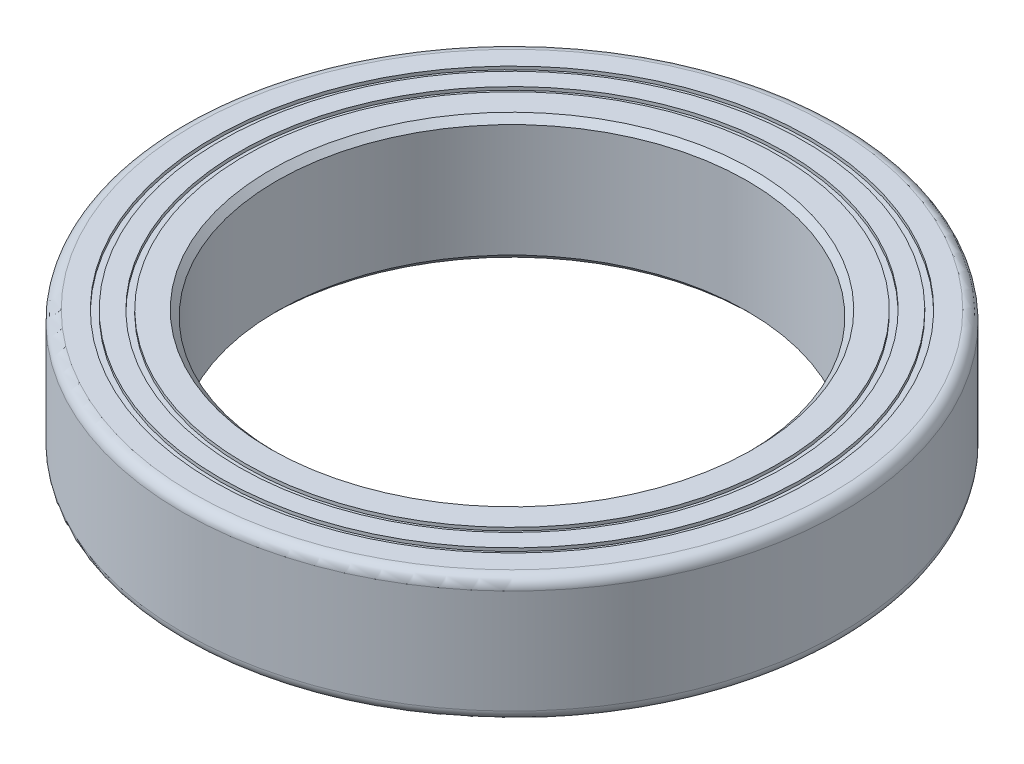
SolidWorks part; units mm, degrees
ref_plane "Front Plane" through (0, 0, 0) normal (0, 0, 1) x (1, 0, 0)
ref_plane "Top Plane" through (0, 0, 0) normal (0, 1, 0) x (1, 0, 0)
ref_plane "Right Plane" through (0, 0, 0) normal (1, 0, 0) x (0, 0, -1)
sketch "Sketch1" plane through (0, 0, 0) normal (0, 0, 1) x (1, 0, 0)
  line L0 (0, 0) -> (7.5, 0) construction
  line L1 (10.5, 0) -> (10.5, 4)
  line L3 (0, 2) -> (0, 0) construction
  line L4 (7.5, 0) -> (7.5, 4)
  line L5 (7.5, 0) -> (8.5, 0)
  line L6 (8.5, 0) -> (8.5, 0.1)
  line L7 (8.5, 0.1) -> (8.7, 0.1)
  line L8 (8.7, 0.1) -> (8.7, 0)
  line L9 (8.7, 0) -> (9.3, 0)
  line L10 (9, 0) -> (9, 2) construction
  line L11 (10.5, 2) -> (7.5, 2) construction
  line L12 (7.5, 2) -> (0, 2) construction
  line L13 (9.3, 0.1) -> (9.3, 0)
  line L14 (9.5, 0.1) -> (9.3, 0.1)
  line L15 (9.5, 0) -> (9.5, 0.1)
  line L16 (10.5, 0) -> (9.5, 0)
  line L17 (10.5, 4) -> (9.5, 4)
  line L18 (9.5, 4) -> (9.5, 3.9)
  line L19 (9.5, 3.9) -> (9.3, 3.9)
  line L20 (9.3, 3.9) -> (9.3, 4)
  line L21 (8.7, 4) -> (9.3, 4)
  line L22 (8.7, 3.9) -> (8.7, 4)
  line L23 (8.5, 3.9) -> (8.7, 3.9)
  line L24 (8.5, 4) -> (8.5, 3.9)
  line L25 (7.5, 4) -> (8.5, 4)
  dimension "D1" = 10.5
  dimension "D2" = 7.5
  dimension "D4" = 1
  dimension "D5" = 0.2
  dimension "D6" = 0.1
  dimension "D3" = 4
revolve "Revolve1" add sketch "Sketch1" angle 360 about L3
fillet "Fillet2" radius 0.344 2 edges at (0, 0, 10.5) (0, 4, 10.5)
chamfer "Chamfer2" distance 0.2 angle 45 2 edges at (0, 0, 7.5) (0, 4, 7.5)
equation "\"Ratio\"= 15"
equation "\"Hull Diameter\"= 92"
equation "\"Fixed Ring Diameter\"= 76"
equation "\"Fixed Pin Diameter\"= 6"
equation "\"Output Ring Diameter\"= 40"
equation "\"Output Pin Diameter\"= 6"
equation "\"Disk Bearing Inner Diameter\"= 9"
equation "\"Disk Bearing Outer Diameter\"= 17"
equation "\"Disk Bearing Height\"= 5"
equation "\"Shaft Bearing Inner Diameter\"= 15"
equation "\"Shaft Bearing Outer Diameter\"= 21"
equation "\"Shaft Bearing Height\"= 4"
equation "\"Eccentricity\"= 1.5"
equation "\"Disk Height\"= 8"
equation "\"Disk Spacing\"= 5"
equation "\"Hull Height\"= 40"
equation "\"Shaft End Bearing Inner Diameter\"= 12"
equation "\"Shaft End Bearing Outer Diameter\"= 18"
equation "\"Shaft End Bearing Height\"= 4"
equation "\"Output Bearing Inner Diameter\"= 55"
equation "\"Output Bearing Outer Diameter\"= 72"
equation "\"Outer Bearing Height\"= 9"
equation "\"D3@Sketch1\"= \"Shaft Bearing Height\""
equation "\"D2@Sketch1\" = \"Shaft Bearing Inner Diameter\" / 2"
equation "\"D1@Sketch1\" = \"Shaft Bearing Outer Diameter\" / 2"
